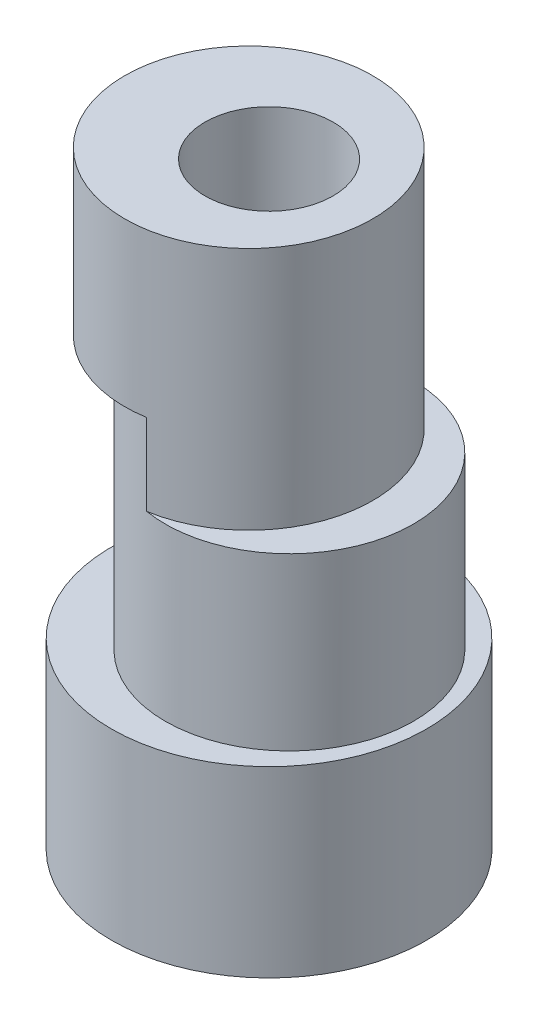
SolidWorks part; units mm, degrees
ref_plane "Front Plane" through (0, 0, 0) normal (0, 0, 1) x (1, 0, 0)
ref_plane "Top Plane" through (0, 0, 0) normal (0, 1, 0) x (1, 0, 0)
ref_plane "Right Plane" through (0, 0, 0) normal (1, 0, 0) x (0, 0, -1)
sketch "Sketch1" plane through (0, 0, 0) normal (0, 1, 0) x (1, 0, 0)
  circle A0 centre (0, 0) radius 7.75
  dimension "D1" = 15.5
extrude "Boss-Extrude1" add sketch "Sketch1" along normal blind 9
sketch "Sketch2" plane through (0, 9, 0) normal (0, 1, 0) x (1, 0, 0)
  line L0 (0, 0) -> (1, 0) construction
  circle A0 centre (1, 0) radius 6.1
  dimension "D2" = 12.2
  dimension "D1" = 1
extrude "Boss-Extrude2" add sketch "Sketch2" along normal blind 12.4
sketch "Sketch4" plane through (0, 21.4, 0) normal (0, 1, 0) x (1, 0, 0)
  line L0 (0, 0) -> (-1, 0) construction
  circle A0 centre (-1, 0) radius 6.1
  dimension "D2" = 12.2
  dimension "D1" = 1
extrude "Boss-Extrude4" add sketch "Sketch4" along normal blind 8
sketch "Sketch5" plane through (0, 0, 0) normal (0, -1, 0) x (1, 0, 0)
  circle A0 centre (0, 0) radius 3.15
  dimension "D1" = 6.3
extrude "Cut-Extrude1" cut sketch "Sketch5" against normal through all
sketch "Sketch8" plane through (0, 0, 0) normal (1, 0, 0) x (0, 0, -1)
  circle A0 centre (0, 5.5) radius 1.5
  dimension "D1" = 3
  dimension "D2" = 5.5
extrude "Cut-Extrude3" cut sketch "Sketch8" against normal through all
sketch "Sketch10" plane through (0, 0, 0) normal (1, 0, 0) x (0, 0, -1)
  line L1 (0, 8.6754) -> (-2.75, 7.0877)
  line L2 (-2.75, 7.0877) -> (-2.75, 3.9123)
  line L3 (-2.75, 3.9123) -> (0, 2.3246)
  line L4 (0, 2.3246) -> (2.75, 3.9123)
  line L5 (2.75, 3.9123) -> (2.75, 7.0877)
  line L6 (2.75, 7.0877) -> (0, 8.6754)
  circle A0 centre (0, 5.5) radius 2.75 construction
  circle A1 centre (0, 5.5) radius 1.5
  circle A2 centre (0, 5.5) radius 1.5
  dimension "D2" = 5.5
  dimension "D1" = 0
extrude "Cut-Extrude4" cut sketch "Sketch10" against normal blind 5.5
sketch "Sketch11" plane through (0, 21.4, 0) normal (0, 1, 0) x (1, 0, 0)
  arc A2 (0, -6.0175) -> (0, 6.0175) centre (-1, 0) ccw
  arc A3 (0, -6.0175) -> (0, 6.0175) centre (1, 0) ccw
  arc A4 (0, -6.0175) -> (0, 6.0175) centre (-1, 0) ccw
  arc A5 (0, -6.0175) -> (0, 6.0175) centre (1, 0) ccw
  dimension "D1" = 0
extrude "Cut-Extrude5" cut sketch "Sketch11" against normal blind 4
